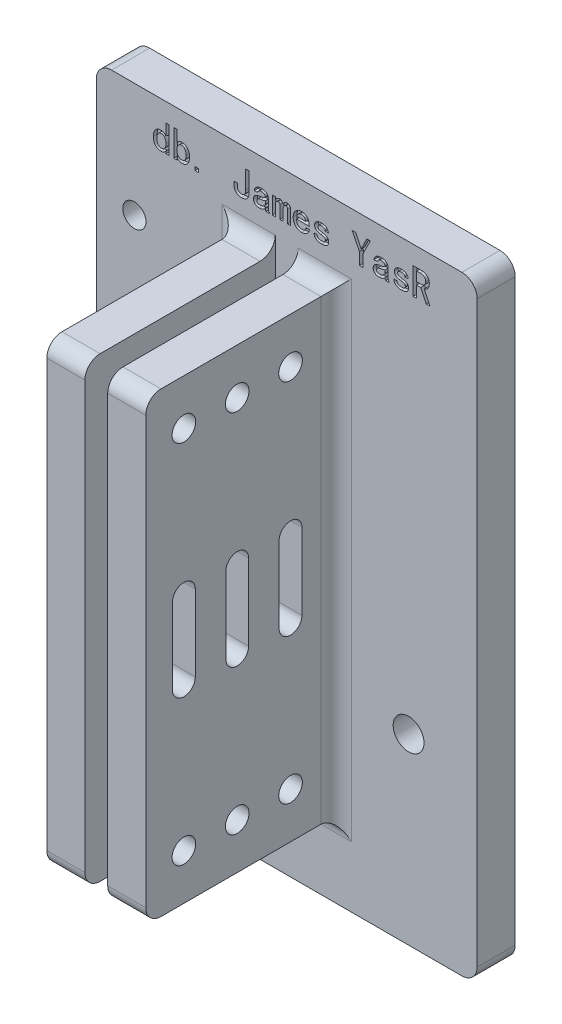
SolidWorks part; units mm, degrees
material "尼龙 101"
ref_plane "前视基准面" through (0, 0, 0) normal (0, 0, 1) x (1, 0, 0)
ref_plane "上视基准面" through (0, 0, 0) normal (0, 1, 0) x (1, 0, 0)
ref_plane "右视基准面" through (0, 0, 0) normal (1, 0, 0) x (0, 0, -1)
other "Configuration Table"
sketch "草图1" plane through (0, 0, 0) normal (0, 1, 0) x (1, 0, 0)
  line L0 (0, 0) -> (0, 25)
  line L1 (0, 30) -> (13, 30)
  line L2 (13, 25) -> (13, 0)
  line L3 (13, 0) -> (8, 0)
  line L4 (8, 0) -> (8, 25)
  line L5 (8, 25) -> (5, 25)
  line L6 (5, 25) -> (5, 0)
  line L7 (5, 0) -> (0, 0)
  line L8 (13, 25) -> (31.5, 25)
  line L9 (31.5, 25) -> (31.5, 30)
  line L10 (31.5, 30) -> (13, 30)
  line L11 (0, 30) -> (-18.5, 30)
  line L12 (-18.5, 30) -> (-18.5, 25)
  line L13 (-18.5, 25) -> (0, 25)
  dimension "D1" = 5
  dimension "D2" = 5
  dimension "D3" = 5
  dimension "D4" = 3
  dimension "D5" = 18.5
  dimension "D6" = 18.5
  dimension "D7" = 25
extrude "凸台-拉伸2" add sketch "草图1" along normal blind 60
sketch "草图2" plane through (0, 60, 0) normal (0, 1, 0) x (1, 0, 0)
  line L1 (-18.5, 25) -> (31.5, 25)
  line L2 (-18.5, 25) -> (-18.5, 30)
  line L3 (-18.5, 30) -> (31.5, 30)
  line L4 (31.5, 25) -> (31.5, 30)
extrude "凸台-拉伸3" add sketch "草图2" along normal blind 10
sketch "草图4" plane through (0, 0, 0) normal (0, -1, 0) x (1, 0, 0)
  line L1 (-18.5, -30) -> (31.5, -30)
  line L2 (-18.5, -30) -> (-18.5, -25)
  line L3 (-18.5, -25) -> (31.5, -25)
  line L4 (31.5, -30) -> (31.5, -25)
extrude "凸台-拉伸5" add sketch "草图4" along normal blind 10
sketch "草图5" plane through (0, 0, -30) normal (0, 0, -1) x (-1, 0, 0)
  line L0 (-31.5, 30) -> (-28.2918, 30) construction
  line L1 (-31.5, 31) -> (18.5, 31) construction
  line L2 (-6.5, 70) -> (-6.5, 56.9973) construction
  line L3 (-31.5, 29) -> (18.5, 29) construction
  line L4 (-23.997, 14) -> (-14.4372, 14) construction
  line L5 (-31.5, 61) -> (18.5, 61) construction
  line L6 (-31.5, 61) -> (-31.5, -1) construction
  line L7 (-31.5, -1) -> (18.5, -1) construction
  line L8 (18.5, 61) -> (18.5, -1) construction
  line L9 (-23.997, 46) -> (-14.4372, 46) construction
  line L10 (-22.5, 8.304) -> (-22.5, 18.6853) construction
  line L11 (9.5, 41.8556) -> (9.5, 48.9545) construction
  circle A0 centre (-22.5, 14) radius 2.025
  circle A1 centre (9.5, 46) radius 2.025
  point P8 (18.5, 30)
  point P9 (-6.5, -1)
  dimension "D10" = 4.05
  dimension "D11" = 4.05
  dimension "D1" = 0
  dimension "D2" = 62
  dimension "D3" = 50
  dimension "D4" = 1
  dimension "D5" = 50
  dimension "D6" = 15
  dimension "D7" = 10.3814
  dimension "D8" = 9
  dimension "D9" = 9
extrude "切除-拉伸1" cut sketch "草图5" against normal through all
fillet "圆角4" radius 2 1 edges at (0, 30, -25)
fillet "圆角5" radius 2 1 edges at (13, 30, -25)
sketch "草图6" plane through (13, 0, 0) normal (1, 0, 0) x (0, 0, -1)
  line L0 (23, 60) -> (25, 60) construction
  line L1 (23, 60) -> (19, 60) construction
  line L2 (0, 60) -> (23, 60) construction
  line L3 (25, 60) -> (25, 54) construction
  line L4 (25, 60) -> (25, 0) construction
  line L5 (25, 30) -> (20.3789, 30) construction
  line L6 (19, 35) -> (19, 25) construction
  line L7 (20.5, 35) -> (20.5, 25)
  line L8 (17.5, 35) -> (17.5, 25)
  line L9 (12, 35) -> (12, 25) construction
  line L10 (13.5, 35) -> (13.5, 25)
  line L11 (10.5, 35) -> (10.5, 25)
  line L12 (5, 35) -> (5, 25) construction
  line L13 (6.5, 35) -> (6.5, 25)
  line L14 (3.5, 35) -> (3.5, 25)
  line L15 (23, 0) -> (23, 60) construction
  circle A0 centre (19, 54) radius 1.55
  arc A1 (20.5, 35) -> (17.5, 35) centre (19, 35) ccw
  arc A2 (17.5, 25) -> (20.5, 25) centre (19, 25) ccw
  circle A3 centre (19, 6) radius 1.55
  circle A4 centre (12, 54) radius 1.55
  circle A5 centre (12, 6) radius 1.55
  arc A6 (13.5, 35) -> (10.5, 35) centre (12, 35) ccw
  arc A7 (10.5, 25) -> (13.5, 25) centre (12, 25) ccw
  circle A8 centre (5, 54) radius 1.55
  circle A9 centre (5, 6) radius 1.55
  arc A10 (6.5, 35) -> (3.5, 35) centre (5, 35) ccw
  arc A11 (3.5, 25) -> (6.5, 25) centre (5, 25) ccw
  point P14 (19, 30)
  point P27 (12, 30)
  point P38 (5, 30)
  dimension "D4" = 3.1
  dimension "D6" = 1.5
  dimension "D7" = 3
  dimension "D1" = 2
  dimension "D2" = 4
  dimension "D3" = 10
  dimension "D5" = 60
  dimension "D8" = 7
extrude "切除-拉伸2" cut sketch "草图6" against normal through all
fillet "圆角6" radius 2 1 edges at (11.5, 60, -25)
fillet "圆角7" radius 2 1 edges at (1.5, 60, -25)
fillet "圆角8" radius 2 2 edges at (1.5, 0, -25) (11.5, 0, -25)
sketch "草图7" plane through (31.5, 0, 0) normal (1, 0, 0) x (0, 0, -1)
  line L0 (25, 30) -> (30, 30) construction
  line L3 (30, 70) -> (30, -10) construction
  circle A0 centre (27.5, 50) radius 1.5
  circle A1 centre (27.5, 10) radius 1.5
  dimension "D1" = 3
  dimension "D2" = 2.5
  dimension "D3" = 20
fillet "圆角9" radius 2 2 edges at (31.5, 70, -27.5) (31.5, -10, -27.5)
fillet "圆角10" radius 2 2 edges at (-18.5, -10, -27.5) (-18.5, 70, -27.5)
fillet "圆角11" radius 2 4 edges at (2.5, 60, 0) (10.5, 60, 0) (2.5, 0, 0) (10.5, 0, 0)
sketch "草图8" plane through (0, 0, -30) normal (0, 0, -1) x (-1, 0, 0)
  line L0 (-31.5, 30) -> (-27.9042, 30) construction
  line L2 (-27.5, 49.6842) -> (-27.5, 18.1895) construction
  line L3 (-31.5, 68) -> (-31.5, -8) construction
  dimension "D1" = 4
sketch "草图9" plane through (0, 0, -30) normal (0, 0, -1) x (-1, 0, 0)
  line L0 (18.5, 50) -> (10.5, 50)
  line L1 (8.5, 52) -> (8.5, 58)
  line L2 (10.5, 60) -> (18.5, 60)
  line L3 (-200031.5, 30) -> (199972.0958, 30) construction
  line L4 (18.5, 68) -> (18.5, -8) construction
  line L5 (18.5, 50) -> (18.5, 60)
  line L6 (-31.5, 30) -> (18.5, 30) construction
  line L8 (18.5, 10) -> (18.5, 0)
  line L9 (10.5, 0) -> (18.5, 0)
  line L10 (18.5, 10) -> (10.5, 10)
  line L11 (8.5, 8) -> (8.5, 2)
  arc A0 (8.5, 58) -> (10.5, 60) centre (10.5, 58) cw
  arc A1 (10.5, 50) -> (8.5, 52) centre (10.5, 52) cw
  arc A2 (10.5, 10) -> (8.5, 8) centre (10.5, 8) ccw
  arc A3 (10.5, 0) -> (8.5, 2) centre (10.5, 2) cw
  point P16 (8.5, 60)
  point P19 (8.5, 50)
  point P22 (8.5, 10)
  point P25 (8.5, 0)
  dimension "D4" = 2
  dimension "D1" = 20
  dimension "D2" = 10
  dimension "D3" = 10
extrude "切除-拉伸3" cut sketch "草图9" against normal blind 2
fillet "圆角12" radius 2 4 edges at (-18.5, 60, -29) (-18.5, 50, -29) (-18.5, 10, -29) (-18.5, 0, -29)
sketch "草图11" plane through (0, 0, -28) normal (0, 0, -1) x (-1, 0, 0)
  line L0 (13.5, 50) -> (13.5, 60) construction
  line L1 (10.5, 50) -> (16.5, 50) construction
  line L2 (16.5, 60) -> (10.5, 60) construction
  line L3 (13.5, 10) -> (13.5, 0) construction
  line L4 (16.5, 10) -> (10.5, 10) construction
  line L5 (10.5, 0) -> (16.5, 0) construction
  circle A0 centre (13.5, 55) radius 1.525
  circle A1 centre (13.5, 5) radius 1.525
  dimension "D1" = 3.05
  dimension "D2" = 3.05
extrude "切除-拉伸4" cut sketch "草图11" against normal through all
sketch "草图12" plane through (0, 0, -30) normal (0, 0, -1) x (-1, 0, 0)
  text T0 "db. James YasR" font "黑体" height 3.5
extrude "切除-拉伸5" cut sketch "草图12" against normal blind 0.5
sketch "草图13" plane through (0, 0, -25) normal (0, 0, 1) x (1, 0, 0)
  text T0 "db. James YasR" font "黑体" height 3.5
extrude "切除-拉伸6" cut sketch "草图13" against normal blind 0.5
